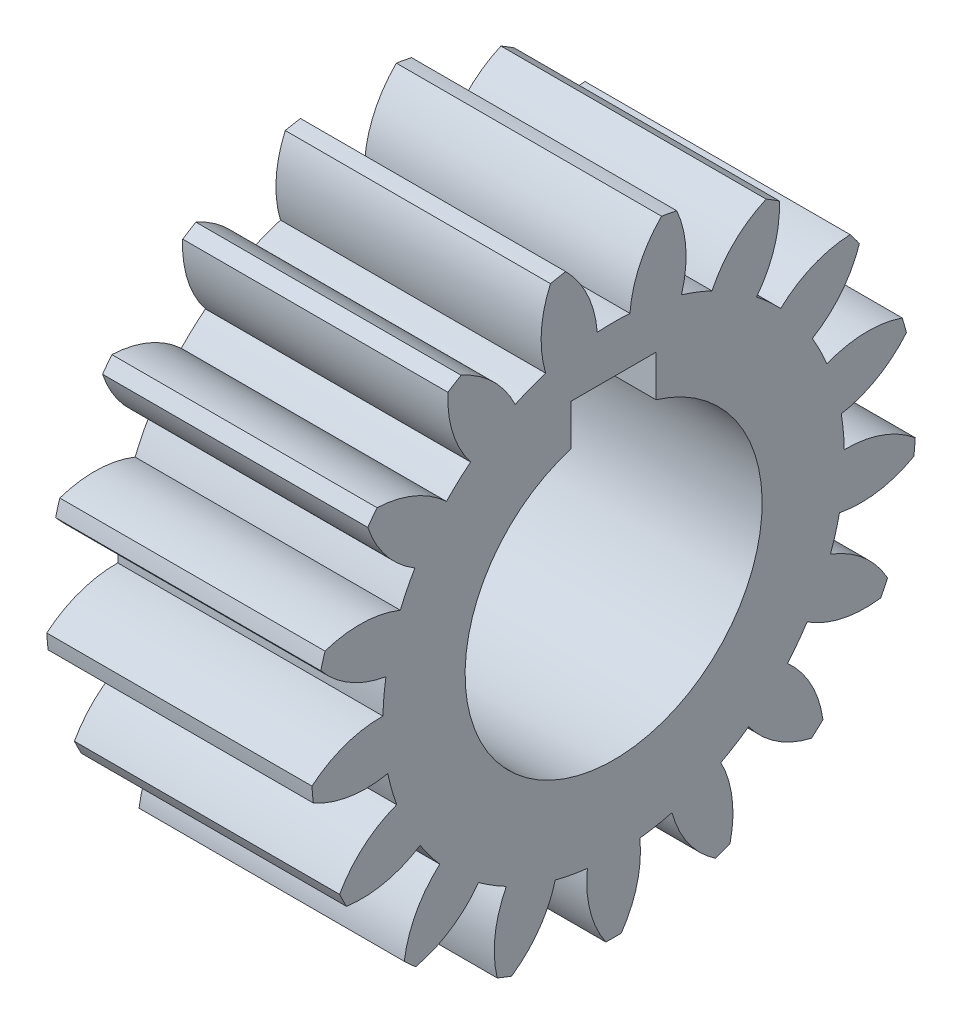
SolidWorks part; units mm, degrees
ref_plane "Plane1" through (0, 0, 0) normal (0, 0, 1) x (1, 0, 0)
ref_plane "Plane2" through (0, 0, 0) normal (0, 1, 0) x (1, 0, 0)
ref_plane "Plane3" through (0, 0, 0) normal (1, 0, 0) x (0, 0, -1)
sketch "HoldingSke" plane through (0, 0, 0) normal (0, 1, 0) x (1, 0, 0)
  line L0 (0, 0) -> (0.3188, -0.0975)
  line L1 (-15, 0) -> (100, 0) construction
  line L2 (0, 0) -> (-2.1039, 2.3779)
  line L3 (0, 0) -> (-11.863, 4.5341)
  line L4 (0, 0) -> (8.2586, 2.5249)
  line L5 (0, 0) -> (-46.8476, -17.4728)
  line L6 (0, 0) -> (-20.7241, -13.9826)
  line L7 (-2.1039, 2.3779) -> (8.6586, 51.2059)
  line L8 (-76.2, 54.61) -> (-72.9, 54.61)
  line L9 (-71.009, 38.7566) -> (-53.1078, 45.2721)
  line L10 (-76.2, 71.12) -> (104.1128, 71.12)
  line L11 (0, 0) -> (-25, 0)
  line L12 (-76.2, 101.6) -> (-76.093, 101.6)
  line L13 (24.9733, 27.94) -> (52.9518, 28.4284)
  line L14 (24.9733, 27.94) -> (24.9743, 27.94)
  line L15 (24.9733, 27.94) -> (100.4006, 29.5858)
  line L16 (-63.627, -3) -> (-12.827, -3)
  circle A0 centre (0, 0) radius 14
  circle A1 centre (0, 0) radius 21.749
  circle A2 centre (0, 0) radius 37.5
  circle A3 centre (0, 0) radius 14
  dimension "MHD" = 43.498
  dimension "Hub_dia" = 75
  dimension "Bore" = 28
  dimension "MBD" = 28
  dimension "Num_teeth" = 17
  dimension "Pitch" = 0.3333
  dimension "Overall_len" = 50
  dimension "Show_teeth" = 17
  dimension "Thickness" = 25
  dimension "OAL" = 50.0001
  dimension "T_dim" = 3.3
  dimension "Ap" = 20
  dimension "H" = 19.05
  dimension "Pitch_radius" = 180.3128
  dimension "Width" = 25
  dimension "Backlash" = 0.107
  dimension "Addendum_fac" = 1
  dimension "Dedendum_fac" = 1.25
  dimension "Clearance_fac" = 0.25
  dimension "Dedendum_add" = 0.001
  dimension "Module" = 3
sketch "BasProSke" plane through (0, 0, 0) normal (0, 1, 0) x (1, 0, 0)
  line L0 (-10, 0) -> (60, 0) construction
  line L1 (0, 0) -> (0, 28.5)
  line L2 (0, 0) -> (25, 0)
  line L3 (25, 0) -> (25, 28.5)
  line L4 (25, 28.5) -> (0, 28.5)
  dimension "Thickness" = 25
  dimension "Diameter" = 57
revolve "Base-Revolve" add sketch "BasProSke" angle 360 about L0
sketch "TooCutSke" plane through (0, 0, 0) normal (1, 0, 0) x (0, 0, -1)
  line L1 (0, 0) -> (0, 107) construction
  line L2 (0, 0) -> (-2.54, 25.3732) construction
  line L3 (0, 0) -> (-9.3374, 49.9505) construction
  line L4 (-2.54, 25.3732) -> (-4.6687, 24.9753) construction
  arc A0 (1.5403, 21.6944) -> (-1.5403, 21.6944) centre (0, 0) ccw
  arc A1 (4.5406, 28.1617) -> (-4.5406, 28.1617) centre (0, 0) ccw
  circle A2 centre (0, 0) radius 25.5 construction
  circle A3 centre (0, 0) radius 23.9622 construction
  arc A4 (-1.5403, 21.6944) -> (-4.5406, 28.1617) centre (-11.7098, 20.9061) ccw
  arc A5 (4.5406, 28.1617) -> (1.5403, 21.6944) centre (11.7098, 20.9061) ccw
  dimension "Root_dia" = 43.498
  dimension "Overcut_dia" = 57.0508
  dimension "Pitch_dia" = 51
  dimension "Base_dia" = 47.9243
  dimension "Flank_rad" = 10.2
  dimension "Half_ang" = 10.588
  dimension "Half_CT" = 2.1656
extrude "ToothCut" cut sketch "TooCutSke" along normal through all
fillet "Breaks" [suppressed] radius 0.06
fillet "RootFillets" [suppressed] radius 0.751
pattern_circular "TeethCuts" count 17 every 21.176 about axis through (-10, 0, 0) along (1, 0, 0) of "ToothCut", "RootFillets", "Breaks"
sketch "HubNeaOneSke" plane through (0, 0, 0) normal (-1, 0, 0) x (0, 0, 1)
  circle A0 centre (0, 0) radius 21.749
  dimension "Diameter" = 43.498
extrude "HubNearOne" [suppressed] add sketch "HubNeaOneSke" along normal blind 25.0001
sketch "HubNeaBotSke" plane through (0, 0, 0) normal (-1, 0, 0) x (0, 0, 1)
  circle A0 centre (0, 0) radius 21.749
  dimension "Diameter" = 43.498
extrude "HubNearBoth" [suppressed] add sketch "HubNeaBotSke" along normal blind 12.5
ref_plane "FarPln" through (25, 0, 0) normal (1, 0, 0) x (0, 0, -1)
sketch "HubFarSke" plane through (25, 0, 0) normal (1, 0, 0) x (0, 0, -1)
  circle A0 centre (0, 0) radius 21.749
  dimension "Diameter" = 43.498
extrude "HubFar" [suppressed] add sketch "HubFarSke" along normal blind 12.5
sketch "BorSke" plane through (0, 0, 0) normal (1, 0, 0) x (0, 0, -1)
  circle A0 centre (0, 0) radius 14
  dimension "Diameter" = 28
extrude "Bore" cut sketch "BorSke" along normal mid plane 100.0001
sketch "KeySke" plane through (0, 0, 0) normal (1, 0, 0) x (0, 0, -1)
  line L0 (-4, 0) -> (-4, 17.3)
  line L1 (-4, 17.3) -> (4, 17.3)
  line L2 (4, 17.3) -> (4, 0)
  line L3 (0, 0) -> (0, 34) construction
  line L4 (-4, 0) -> (4, 0)
  dimension "Offset" = 17.3
  dimension "Width" = 8
extrude "Keyway" cut sketch "KeySke" along normal mid plane 100.0001
pattern_circular "Keyway2" [suppressed] count 2 every 90 about axis through (-10, 0, 0) along (1, 0, 0)
equation "' \"Module@HoldingSke\" = 6.35"
equation "' \"Num_teeth@HoldingSke\" = 12"
equation "' \"Ap@HoldingSke\" =  20"
equation "' \"Ap@HoldingSke\" = 20"
equation "' \"Width@HoldingSke\" = 0.5 * 25.4"
equation "' \"Hub_dia@HoldingSke\"= 1 * 25.4"
equation "' \"Hub_dia@HoldingSke\" = 1 * 25.4"
equation "' \"Overall_len@HoldingSke\" = 1.0 * 25.4"
equation "' \"Bore@HoldingSke\" = 0.75 * 25.4"
equation "' \"T_dim@HoldingSke\" = 0.1 * 25.4"
equation "' \"Width@KeySke\" = 0.25 * 25.4"
equation "' \"Show_teeth@HoldingSke\" = 13"
equation "' \"Backlash@HoldingSke\" = 0.009 * 25.4"
equation "' \"Addendum_fac@HoldingSke\" = 1.0"
equation "' \"Dedendum_fac@HoldingSke\" = 1.25"
equation "' \"Dedendum_add@HoldingSke\" = 0.00005 * 25.4"
equation "' \"Clearance_fac@HoldingSke\" = 0.25"
equation "\"Pitch@HoldingSke\" = 1 / \"Module@HoldingSke\""
equation "\"Overcut_dia@TooCutSke\" = (\"Num_teeth@HoldingSke\" + 2 * \"Addendum_fac@HoldingSke\") / \"Pitch@HoldingSke\" + 0.002 * 25.4"
equation "\"Pitch_dia@TooCutSke\" = \"Num_teeth@HoldingSke\" / \"Pitch@HoldingSke\""
equation "\"Base_dia@TooCutSke\" = \"Num_teeth@HoldingSke\" / \"Pitch@HoldingSke\" * cos((\"Ap@HoldingSke\"  * 3.14159265 / 180))"
equation "\"Root_dia@TooCutSke\" = (\"Num_teeth@HoldingSke\" + 2) / \"Pitch@HoldingSke\" - 2 * (\"Addendum_fac@HoldingSke\" + \"Dedendum_fac@HoldingSke\") / \"Pitch@HoldingSke\" - \"Dedendum_add@HoldingSke\" * 2"
equation "\"Half_ang@TooCutSke\" = 180 / \"Num_teeth@HoldingSke\""
equation "\"Half_CT@TooCutSke\" = \"Num_teeth@HoldingSke\" / \"Pitch@HoldingSke\" * sin((3.14159265 / 2 / \"Num_teeth@HoldingSke\")) / 2 - 7 * \"Backlash@HoldingSke\" / 4"
equation "\"Flank_rad@TooCutSke\" = \"Num_teeth@HoldingSke\" / \"Pitch@HoldingSke\" / 5"
equation "\"Radius@RootFillets\" = \"Clearance_fac@HoldingSke\" / \"Pitch@HoldingSke\" + \"Dedendum_add@HoldingSke\""
equation "\"Break_rad@Breaks\" = 0.02 / \"Pitch@HoldingSke\""
equation "\"Thickness@HoldingSke\" = \"Width@HoldingSke\""
equation "\"OAL@HoldingSke\" = \"Thickness@HoldingSke\""
equation "\"MHD@HoldingSke\" = (\"Num_teeth@HoldingSke\" + 2) / \"Pitch@HoldingSke\" - 2 * (\"Addendum_fac@HoldingSke\" + \"Dedendum_fac@HoldingSke\")  / \"Pitch@HoldingSke\" - \"Dedendum_add@HoldingSke\" * 2"
equation "\"MBD@HoldingSke\" = (\"Num_teeth@HoldingSke\" + 2) / \"Pitch@HoldingSke\" - 2 * (\"Addendum_fac@HoldingSke\" + \"Dedendum_fac@HoldingSke\")  / \"Pitch@HoldingSke\" - \"Dedendum_add@HoldingSke\" * 2 - 0.002 * 25.4"
equation "\"MHD@HoldingSke\" = ((sgn( \"MHD@HoldingSke\" - \"Hub_dia@HoldingSke\" )-1)*( \"MHD@HoldingSke\" - \"Hub_dia@HoldingSke\" ))/-2+ \"Hub_dia@HoldingSke\""
equation "\"MBD@HoldingSke\" = ((sgn( \"MBD@HoldingSke\" - \"Bore@HoldingSke\" )-1)*( \"MBD@HoldingSke\" - \"Bore@HoldingSke\" ))/-2+ \"Bore@HoldingSke\""
equation "\"OAL@HoldingSke\" = ((sgn( \"OAL@HoldingSke\" - \"Overall_len@HoldingSke\" )+1)*( \"OAL@HoldingSke\" - \"Overall_len@HoldingSke\" ))/2 + \"Overall_len@HoldingSke\" + 0.000002 * 25.4"
equation "\"Num_teeth@TeethCuts\" = int( \"Show_teeth@HoldingSke\" ) + 1"
equation "\"Num_teeth@TeethCuts\" = ((sgn( \"Num_teeth@TeethCuts\" - \"Num_teeth@HoldingSke\" )-1)*( \"Num_teeth@TeethCuts\" - \"Num_teeth@HoldingSke\" ))/-2+ \"Num_teeth@HoldingSke\""
equation "\"Num_teeth@TeethCuts\" = ((sgn( \"Num_teeth@TeethCuts\" - 2.0)+1)*( \"Num_teeth@TeethCuts\" - 2.0))/2 +2.0"
equation "\"Angle@TeethCuts\" = 360.0 / \"Num_teeth@HoldingSke\""
equation "\"Diameter@BasProSke\" = (\"Num_teeth@HoldingSke\" + 2 * \"Addendum_fac@HoldingSke\") / \"Pitch@HoldingSke\""
equation "\"Thickness@BasProSke\"  = \"Thickness@HoldingSke\""
equation "' \"Fillet_rad@BasProSke\" =  \"Thickness@HoldingSke\" * 0.05"
equation "' \"Fillet_rad@BasProSke\" = \"Thickness@HoldingSke\" * 0.05"
equation "\"MHD@HoldingSke\" = ((sgn( \"MHD@HoldingSke\" - \"Root_dia@TooCutSke\" )-1)*( \"MHD@HoldingSke\" - \"Root_dia@TooCutSke\" ))/-2+ \"Root_dia@TooCutSke\""
equation "\"Diameter@HubNeaOneSke\" = \"MHD@HoldingSke\""
equation "\"Length@HubNearOne\" = \"OAL@HoldingSke\" - \"Thickness@BasProSke\""
equation "\"Diameter@HubNeaBotSke\" = \"MHD@HoldingSke\""
equation "\"Length@HubNearBoth\" = ( \"OAL@HoldingSke\" - \"Thickness@BasProSke\" ) / 2.0"
equation "\"Thickness@FarPln\" = \"Thickness@BasProSke\""
equation "\"Diameter@HubFarSke\" = \"MHD@HoldingSke\""
equation "\"Length@HubFar\" = ( \"OAL@HoldingSke\" - \"Thickness@BasProSke\" ) / 2.0"
equation "\"Diameter@BorSke\" = \"MBD@HoldingSke\""
equation "\"D1@Bore\" = \"OAL@HoldingSke\" * 2.0"
equation "\"D1@Keyway\" = \"OAL@HoldingSke\" * 2.0"
equation "\"Offset@KeySke\" = \"T_dim@HoldingSke\" + \"MBD@HoldingSke\" / 2.0"
